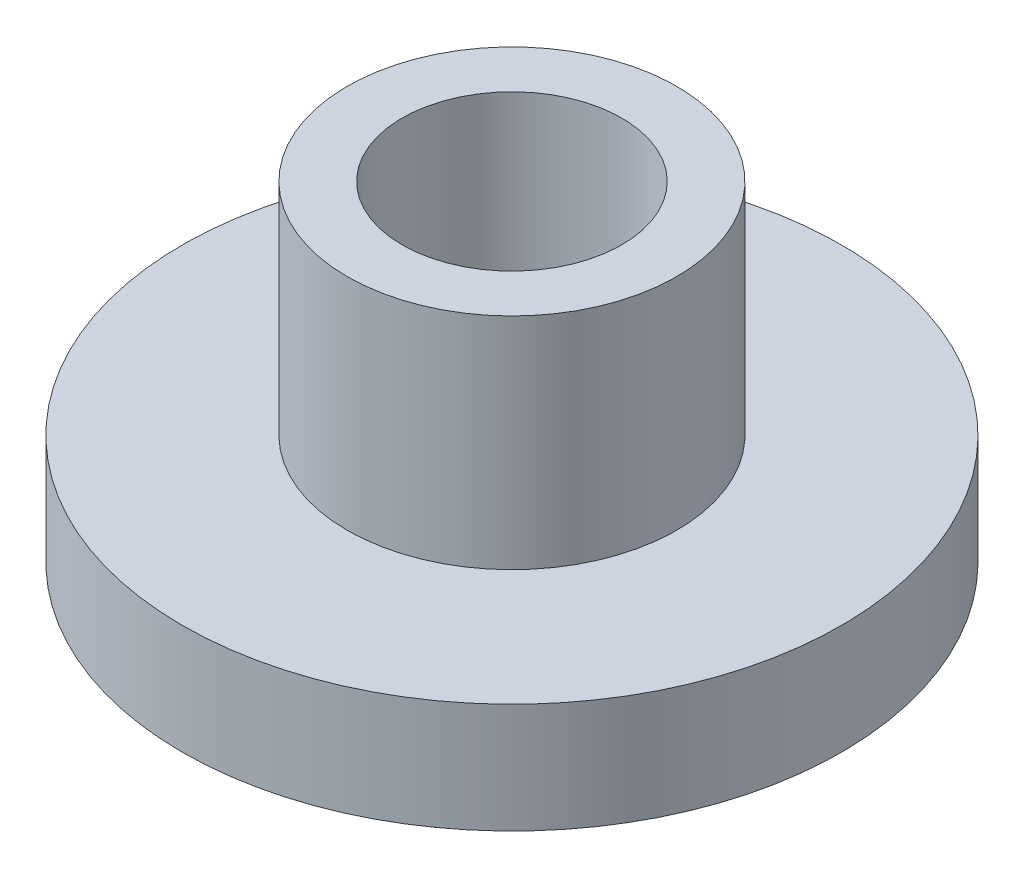
SolidWorks part; units mm, degrees
ref_plane "Front" through (0, 0, 0) normal (0, 0, 1) x (1, 0, 0)
ref_plane "Top" through (0, 0, 0) normal (0, 1, 0) x (1, 0, 0)
ref_plane "Right" through (0, 0, 0) normal (1, 0, 0) x (0, 0, -1)
sketch "Sketch1" plane through (0, 0, 0) normal (0, 1, 0) x (1, 0, 0)
  circle A0 centre (0, 0) radius 38.1
  dimension "D1" = 76.2
extrude "Extrude1" add sketch "Sketch1" along normal blind 12.7
sketch "Sketch2" plane through (0, 12.7, 0) normal (0, 1, 0) x (-1, 0, 0)
  circle A0 centre (0, 0) radius 19.05
  dimension "D1" = 38.1
extrude "Extrude2" add sketch "Sketch2" along normal blind 25.4
sketch "Sketch3" plane through (0, 38.1, 0) normal (0, 1, 0) x (-1, 0, 0)
  circle A0 centre (0, 0) radius 12.7
  dimension "D1" = 25.4
extrude "Cut-Extrude1" cut sketch "Sketch3" against normal through all
